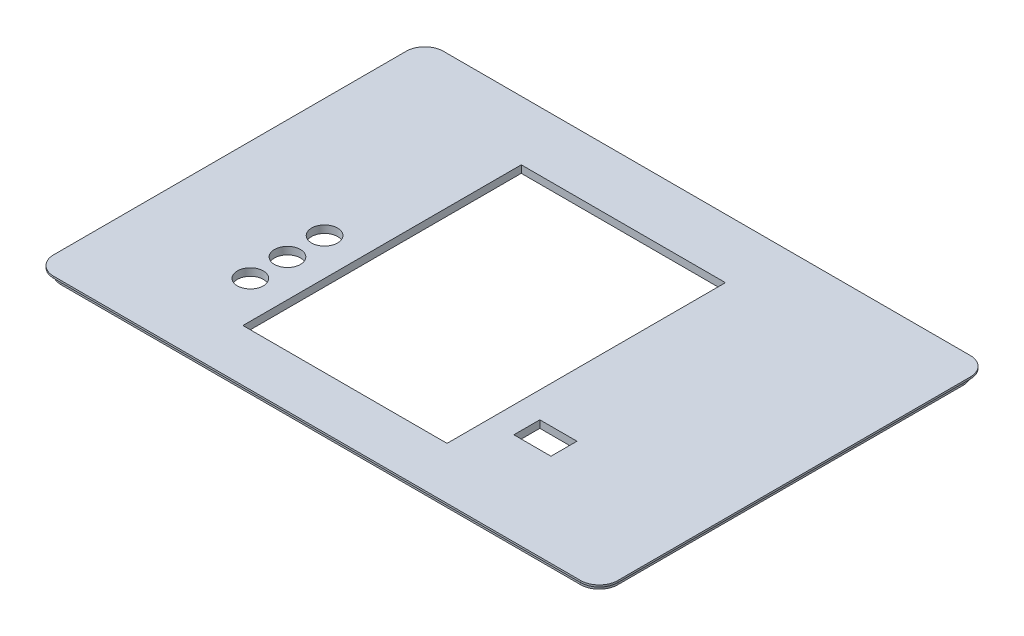
SolidWorks part; units mm, degrees
ref_plane "前视基准面" through (0, 0, 0) normal (0, 0, 1) x (1, 0, 0)
ref_plane "上视基准面" through (0, 0, 0) normal (0, 1, 0) x (1, 0, 0)
ref_plane "右视基准面" through (0, 0, 0) normal (1, 0, 0) x (0, 0, -1)
other "Configuration Table"
sketch "草图16" plane through (0, 0, 0) normal (0, 1, 0) x (1, 0, 0)
  line L1 (71, -52.5) -> (-71, -52.5)
  line L2 (76, -47.5) -> (76, 47.5)
  line L3 (71, 52.5) -> (-71, 52.5)
  line L4 (-76, -47.5) -> (-76, 47.5)
  line L5 (76, -52.5) -> (-76, 52.5) construction
  line L6 (76, 52.5) -> (-76, -52.5) construction
  arc A0 (-71, -52.5) -> (-76, -47.5) centre (-71, -47.5) cw
  arc A1 (71, -52.5) -> (76, -47.5) centre (71, -47.5) ccw
  arc A2 (76, 47.5) -> (71, 52.5) centre (71, 47.5) ccw
  arc A3 (-71, 52.5) -> (-76, 47.5) centre (-71, 47.5) ccw
  point P0 (0, 0)
  dimension "D3" = 5
  dimension "D1" = 152
  dimension "D2" = 105
extrude "凸台-拉伸5" add sketch "草图16" along normal blind 0.5
sketch "草图18" plane through (0, 0, 0) normal (0, -1, 0) x (1, 0, 0)
  line L1 (70, -51.5) -> (-70, -51.5)
  line L2 (75, -46.5) -> (75, 46.5)
  line L3 (70, 51.5) -> (-70, 51.5)
  line L4 (-75, -46.5) -> (-75, 46.5)
  line L5 (75, -51.5) -> (-75, 51.5) construction
  line L6 (75, 51.5) -> (-75, -51.5) construction
  arc A0 (-70, -51.5) -> (-75, -46.5) centre (-70, -46.5) cw
  arc A1 (70, -51.5) -> (75, -46.5) centre (70, -46.5) ccw
  arc A2 (75, 46.5) -> (70, 51.5) centre (70, 46.5) ccw
  arc A3 (-70, 51.5) -> (-75, 46.5) centre (-70, 46.5) ccw
  point P0 (0, 0)
  dimension "D3" = 5
  dimension "D1" = 150
  dimension "D2" = 103
extrude "凸台-拉伸6" add sketch "草图18" along normal blind 1.5
sketch "草图19" plane through (0, 0.5, 0) normal (0, 1, 0) x (1, 0, 0)
  line L0 (71, 52.5) -> (-71, 52.5) construction
  line L1 (-34, 36.5) -> (21, 36.5)
  line L2 (-34, 36.5) -> (-34, -38.5)
  line L3 (-34, -38.5) -> (21, -38.5)
  line L4 (21, 36.5) -> (21, -38.5)
  line L5 (76, -47.5) -> (76, 47.5) construction
  dimension "D1" = 16
  dimension "D2" = 75
  dimension "D3" = 55
  dimension "D4" = 55
extrude "切除-拉伸10" cut sketch "草图19" against normal blind 33
sketch "草图20" plane through (0, 0.5, 0) normal (0, 1, 0) x (1, 0, 0)
  line L1 (28, -20.5) -> (38, -20.5)
  line L2 (28, -20.5) -> (28, -27.5)
  line L3 (28, -27.5) -> (38, -27.5)
  line L4 (38, -20.5) -> (38, -27.5)
  line L5 (71, 52.5) -> (-71, 52.5) construction
  line L6 (76, -47.5) -> (76, 47.5) construction
  dimension "D1" = 38
  dimension "D2" = 73
  dimension "D3" = 10
  dimension "D4" = 7
extrude "切除-拉伸11" cut sketch "草图20" against normal blind 33
sketch "草图21" plane through (0, 0.5, 0) normal (0, 1, 0) x (1, 0, 0)
  line L0 (71, 52.5) -> (-71, 52.5) construction
  line L1 (76, -47.5) -> (76, 47.5) construction
  circle A0 centre (-44, -6.5) radius 3.5
  circle A1 centre (-44, -16.5) radius 3.5
  circle A2 centre (-44, -26.5) radius 3.5
  dimension "D1" = 59
  dimension "D3" = 10
  dimension "D2" = 120
  dimension "D4" = 10
extrude "切除-拉伸12" cut sketch "草图21" against normal blind 33
